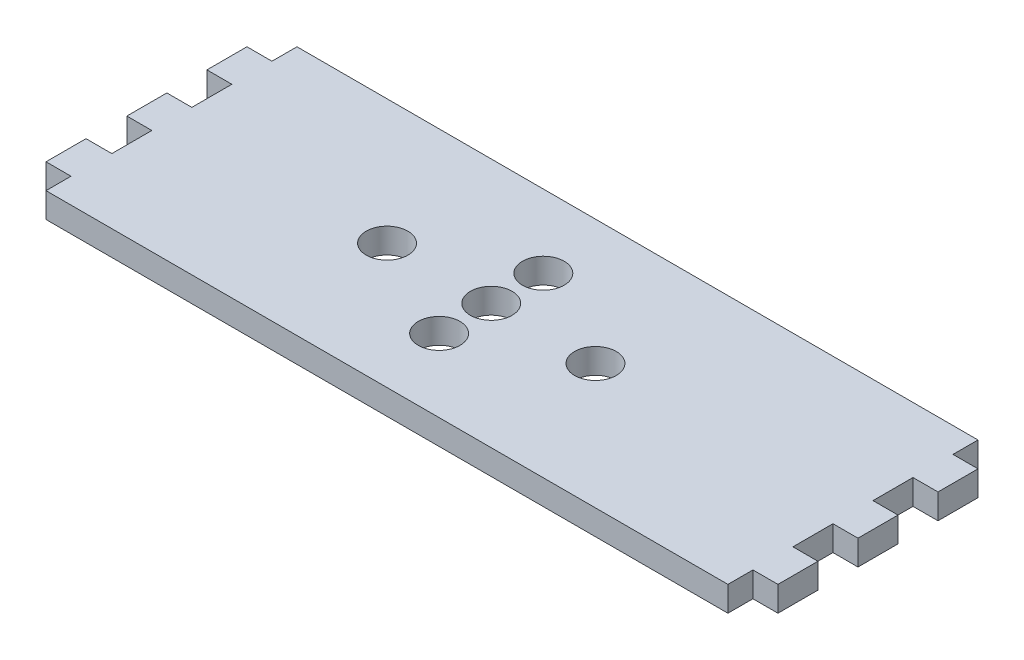
SolidWorks part; units mm, degrees
ref_plane "Front" through (0, 0, 0) normal (0, 0, 1) x (1, 0, 0)
ref_plane "Top" through (0, 0, 0) normal (0, 1, 0) x (1, 0, 0)
ref_plane "Right" through (0, 0, 0) normal (1, 0, 0) x (0, 0, -1)
sketch "Esboço1" plane through (0, 0, 0) normal (0, 1, 0) x (1, 0, 0)
  line L0 (-57.9249, 7.8938) -> (-54.9249, 7.8938)
  line L1 (-54.9249, 7.8938) -> (-54.9249, 10.8938)
  line L2 (-54.9249, 10.8938) -> (26.7684, 10.8938)
  line L3 (26.7684, 10.8938) -> (26.7684, 7.8938)
  line L4 (26.7684, 7.8938) -> (29.7684, 7.8938)
  line L6 (29.7704, -16.1059) -> (26.7704, -16.1059)
  line L7 (26.7704, -16.1059) -> (26.7704, -19.1059)
  line L8 (26.7704, -19.1059) -> (-55.0296, -19.1059)
  line L9 (-55.0296, -19.1059) -> (-55.0296, -16.1059)
  line L10 (-55.0296, -16.1059) -> (-58.0296, -16.1059)
  line L17 (-57.9312, -6.5062) -> (-54.9312, -6.5062)
  line L18 (-54.9312, -6.5062) -> (-54.9312, -11.3062)
  line L19 (-54.9312, -11.3062) -> (-58.0296, -11.3062)
  line L24 (-58.0296, -11.3062) -> (-58.0296, -16.1059)
  line L30 (-57.9249, 7.8938) -> (-57.9249, 3.0938)
  line L31 (-57.9249, 3.0938) -> (-54.9342, 3.0938)
  line L32 (-54.9342, 3.0938) -> (-54.9342, -1.7062)
  line L33 (-54.9342, -1.7062) -> (-57.9312, -1.7062)
  line L40 (29.7684, 7.8938) -> (29.7684, 3.0938)
  line L41 (29.7684, 3.0938) -> (26.7704, 3.0938)
  line L42 (26.7704, 3.0938) -> (26.7704, -1.7062)
  line L43 (26.7704, -1.7062) -> (29.7704, -1.7062)
  line L48 (29.7704, -1.7062) -> (29.7704, -6.5062)
  line L49 (29.7704, -6.5062) -> (26.7704, -6.5062)
  line L50 (26.7704, -6.5062) -> (26.7704, -11.3062)
  line L51 (26.7704, -11.3062) -> (29.7704, -11.3062)
  line L56 (29.7704, -11.3062) -> (29.7704, -16.1059)
  line L57 (-57.9312, -1.7062) -> (-57.9312, -6.5062)
  circle A0 centre (-16.6213, -4.1059) radius 2.5
  circle A1 centre (-16.6213, 2.1441) radius 2.5
  circle A2 centre (-4.1213, -4.1059) radius 2.5
  circle A3 centre (-16.6213, -10.3559) radius 2.5
  circle A4 centre (-29.1213, -4.1059) radius 2.5
  dimension "D12" = 5
  dimension "D13" = 5
  dimension "D14" = 5
  dimension "D15" = 5
  dimension "D16" = 5
  dimension "D17" = 0
  dimension "D18" = 6.25
  dimension "D19" = 6.25
  dimension "D20" = 12.5
  dimension "D21" = 15
  dimension "D22" = 4.8
  dimension "D37" = 10.8938
  dimension "D35" = 12.5
  dimension "D36" = 15
  dimension "D26" = 15
  dimension "D2" = 81.8
  dimension "D3" = 24
  dimension "D4" = 3
  dimension "D5" = 3
  dimension "D6" = 3
  dimension "D7" = 3
  dimension "D8" = 3
  dimension "D9" = 3
  dimension "D10" = 3
  dimension "D11" = 3
  dimension "D23" = 4.8
  dimension "D24" = 4.8
  dimension "D25" = 4.8
  dimension "D27" = 4.8
  dimension "D28" = 4.8
  dimension "D29" = 4.8
  dimension "D31" = 3
  dimension "D32" = 3
  dimension "D33" = 4.8
  dimension "D34" = 2.998
extrude "Ressalto-extrusão1" add sketch "Esboço1" along normal blind 3
